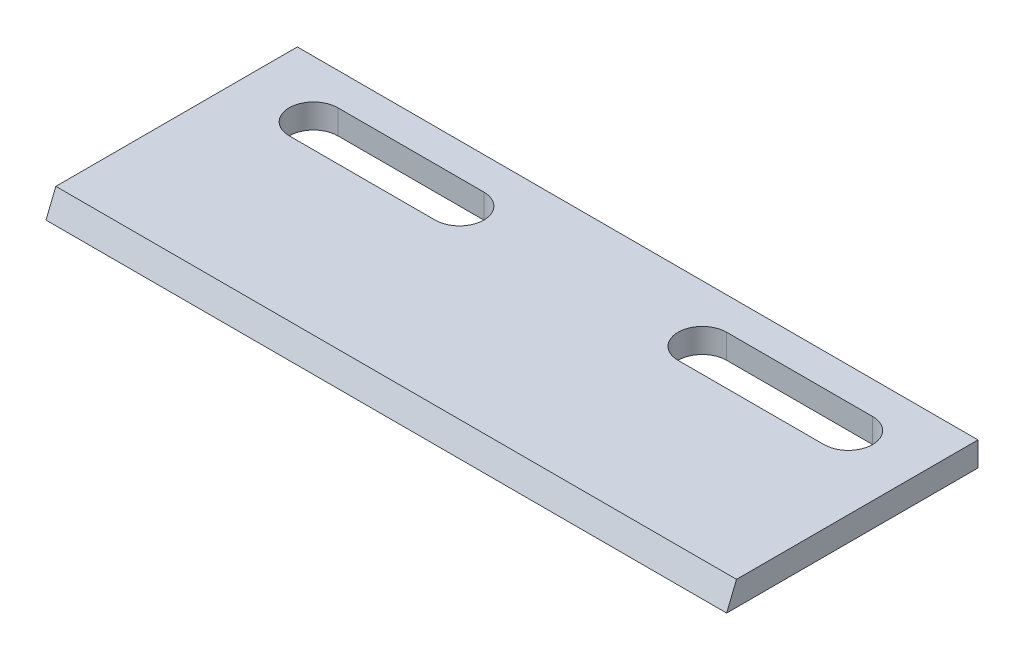
SolidWorks part; units mm, degrees
material "Beech"
ref_plane "Front Plane" through (0, 0, 0) normal (0, 0, 1) x (1, 0, 0)
ref_plane "Top Plane" through (0, 0, 0) normal (0, 1, 0) x (1, 0, 0)
ref_plane "Right Plane" through (0, 0, 0) normal (1, 0, 0) x (0, 0, -1)
sketch "Sketch1" plane through (0, 3140.71, 0) normal (0, 1, 0) x (1, 0, 0)
  line L1 (266.573, 7002.78) -> (-266.573, 7002.78)
  line L2 (266.573, 7002.78) -> (266.573, 6805.9166)
  line L3 (266.573, 6805.9166) -> (-266.573, 6805.9166)
  line L4 (-266.573, 7002.78) -> (-266.573, 6805.9166)
extrude "Boss-Extrude1" add sketch "Sketch1" along normal blind 19.05
sketch "Sketch2" plane through (266.573, 0, 0) normal (1, 0, 0) x (0, 0, -1)
  line L0 (6805.9166, 3140.71) -> (6813.6133, 3159.76)
  line L1 (6805.9166, 3159.76) -> (7002.78, 3159.76) construction
  line L2 (6813.6133, 3159.76) -> (6805.9166, 3159.76)
  line L3 (6805.9166, 3159.76) -> (6805.9166, 3140.71)
  line L4 (6621.1958, 2683.51) -> (6805.9166, 3140.71) construction
extrude "Cut-Extrude1" cut sketch "Sketch2" against normal through all
sketch "Sketch3" plane through (0, 3159.76, 0) normal (0, 1, 0) x (1, 0, 0)
  line L0 (209.423, 6958.33) -> (95.123, 6958.33) construction
  line L1 (209.423, 6939.28) -> (95.123, 6939.28)
  line L2 (209.423, 6977.38) -> (95.123, 6977.38)
  line L4 (266.573, 7002.78) -> (-266.573, 7002.78) construction
  line L5 (266.573, 6813.6133) -> (266.573, 7002.78) construction
  line L6 (0, 7002.78) -> (0, 6813.6133) construction
  line L7 (-266.573, 6813.6133) -> (266.573, 6813.6133) construction
  line L8 (-209.423, 6958.33) -> (-95.123, 6958.33) construction
  line L9 (-209.423, 6939.28) -> (-95.123, 6939.28)
  line L10 (-209.423, 6977.38) -> (-95.123, 6977.38)
  arc A0 (209.423, 6939.28) -> (209.423, 6977.38) centre (209.423, 6958.33) ccw
  arc A1 (95.123, 6977.38) -> (95.123, 6939.28) centre (95.123, 6958.33) ccw
  arc A2 (-209.423, 6939.28) -> (-209.423, 6977.38) centre (-209.423, 6958.33) cw
  arc A3 (-95.123, 6977.38) -> (-95.123, 6939.28) centre (-95.123, 6958.33) cw
  point P2 (152.273, 6958.33)
  point P17 (-152.273, 6958.33)
  dimension "D1" = 38.1
  dimension "D2" = 25.4
  dimension "D3" = 114.3
  dimension "D4" = 114.3
extrude "Cut-Extrude2" cut sketch "Sketch3" against normal through all
